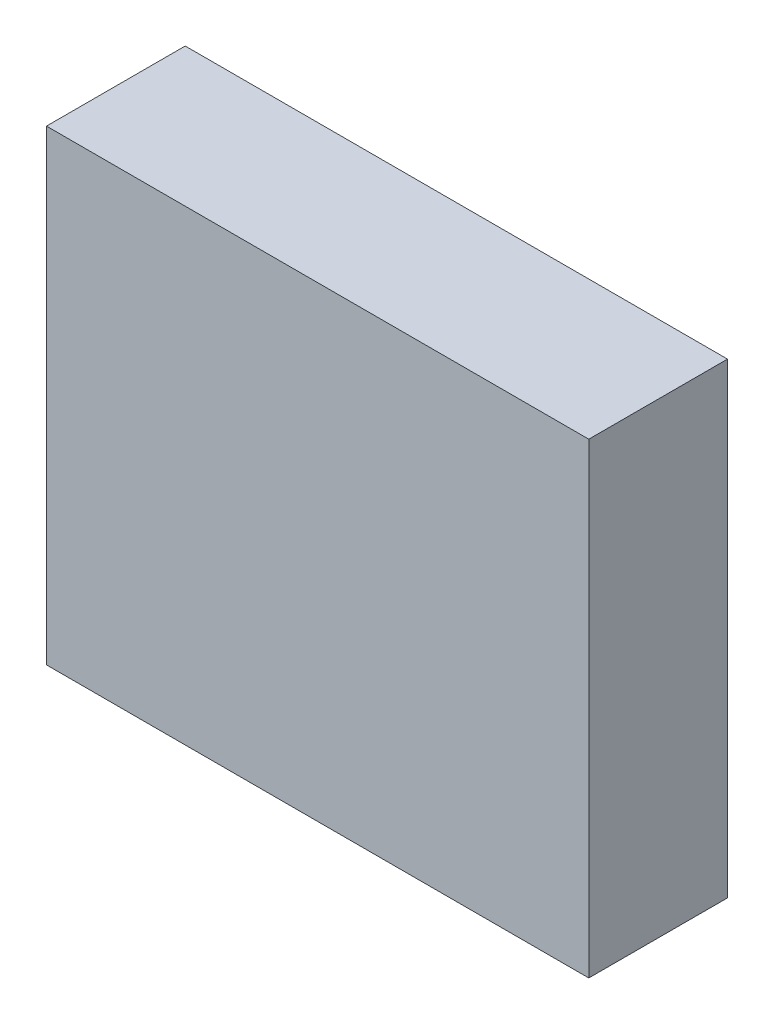
SolidWorks part; units mm, degrees
ref_plane "前视基准面" through (0, 0, 0) normal (0, 0, 1) x (1, 0, 0)
ref_plane "上视基准面" through (0, 0, 0) normal (0, 1, 0) x (1, 0, 0)
ref_plane "右视基准面" through (0, 0, 0) normal (1, 0, 0) x (0, 0, -1)
other "Configuration Table"
sketch "草图1" plane through (0, 0, 0) normal (0, 0, 1) x (1, 0, 0)
  line L1 (-43, -37) -> (43, -37)
  line L2 (-43, -37) -> (-43, 37)
  line L3 (-43, 37) -> (43, 37)
  line L4 (43, -37) -> (43, 37)
extrude "凸台-拉伸1" add sketch "草图1" against normal blind 22
